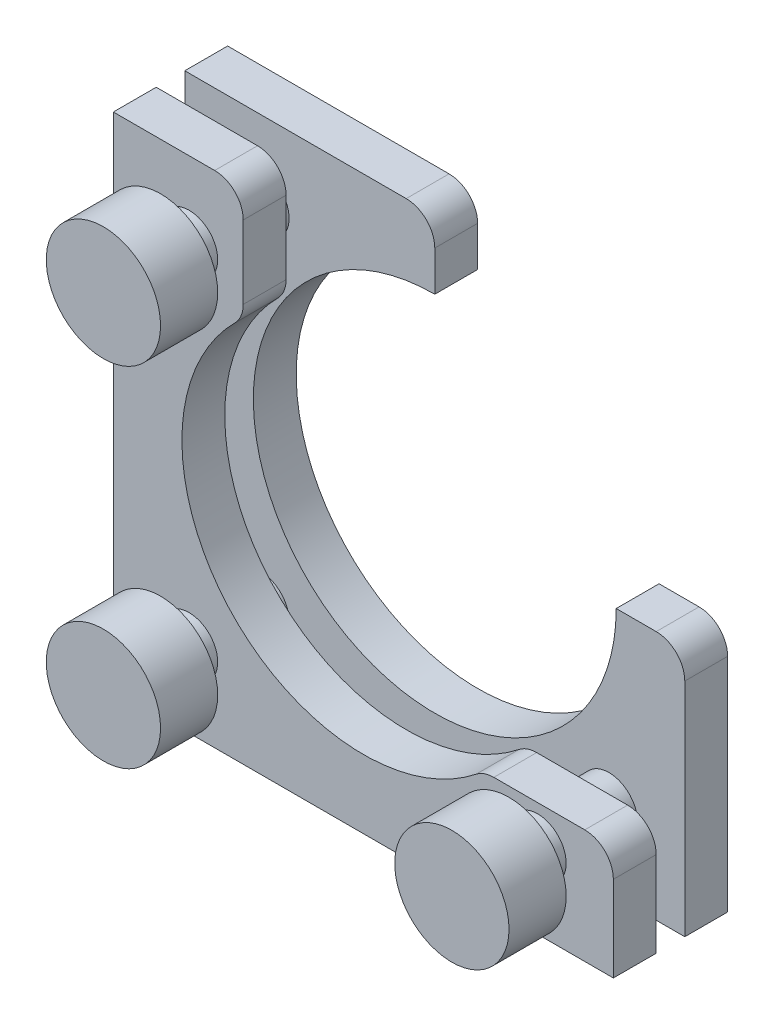
SolidWorks part; units mm, degrees
ref_plane "前视基准面" through (0, 0, 0) normal (0, 0, 1) x (1, 0, 0)
ref_plane "上视基准面" through (0, 0, 0) normal (0, 1, 0) x (1, 0, 0)
ref_plane "右视基准面" through (0, 0, 0) normal (1, 0, 0) x (0, 0, -1)
sketch "草图1" plane through (0, 0, 0) normal (0, 0, 1) x (1, 0, 0)
  line L1 (-17.5, 17.5) -> (17.5, 17.5)
  line L2 (-17.5, 17.5) -> (-17.5, -17.5)
  line L3 (-17.5, -17.5) -> (17.5, -17.5)
  line L4 (17.5, 17.5) -> (17.5, -17.5)
  line L5 (-17.5, 17.5) -> (17.5, -17.5) construction
  line L6 (-17.5, -17.5) -> (17.5, 17.5) construction
  circle A0 centre (0, 0) radius 12.7
  point P0 (0, 0)
  dimension "D1" = 25.4
  dimension "D2" = 35
  dimension "D3" = 35
extrude "凸台-拉伸1" add sketch "草图1" along normal blind 3
sketch "草图2" plane through (0, 0, 3) normal (0, 0, 1) x (1, 0, 0)
  line L0 (-17.5, 17.5) -> (17.5, -17.5)
  line L1 (17.5, -17.5) -> (17.5, 17.5)
  line L2 (17.5, 17.5) -> (-17.5, -17.5)
  circle A0 centre (-17.5, 17.5) radius 7.5
  circle A1 centre (-17.5, -17.5) radius 7.5
  circle A2 centre (17.5, -17.5) radius 7.5
  circle A3 centre (-12.1967, 12.1967) radius 2
  circle A4 centre (12.1967, -12.1967) radius 2
  circle A5 centre (-12.1967, -12.1967) radius 2
  dimension "D1" = 15
  dimension "D2" = 15
  dimension "D3" = 15
extrude "凸台-拉伸2" add sketch "草图2" along normal blind 2 and the other way blind 5 contours A3 | A5 | A4
sketch "草图3" plane through (0, 0, 5) normal (0, 0, 1) x (1, 0, 0)
  circle A0 centre (-12.1967, 12.1967) radius 4
  circle A1 centre (-12.1967, -12.1967) radius 4
  circle A2 centre (12.1967, -12.1967) radius 4
extrude "凸台-拉伸3" add sketch "草图3" along normal blind 4
sketch "草图4" plane through (0, 0, -2) normal (0, 0, -1) x (-1, 0, 0)
  line L1 (-17.5, -17.5) -> (17.5, -17.5)
  line L2 (-17.5, -17.5) -> (-17.5, 17.5)
  line L3 (-17.5, 17.5) -> (17.5, 17.5)
  line L4 (17.5, -17.5) -> (17.5, 17.5)
  line L5 (-17.5, -17.5) -> (17.5, 17.5) construction
  line L6 (-17.5, 17.5) -> (17.5, -17.5) construction
  circle A0 centre (0, 0) radius 12.7
  point P0 (0, 0)
extrude "凸台-拉伸4" add sketch "草图4" along normal blind 3
sketch "草图5" plane through (0, 0, 3) normal (0, 0, 1) x (1, 0, 0)
  line L1 (43.4081, 44.5181) -> (-8.4081, 44.5181)
  line L2 (43.4081, 44.5181) -> (43.4081, -9.5181)
  line L3 (43.4081, -9.5181) -> (-8.4081, -9.5181)
  line L4 (-8.4081, 44.5181) -> (-8.4081, -9.5181)
  line L5 (43.4081, 44.5181) -> (-8.4081, -9.5181) construction
  line L6 (43.4081, -9.5181) -> (-8.4081, 44.5181) construction
  circle A0 centre (0, 0) radius 12.7 construction
  point P0 (17.5, 17.5)
extrude "切除-拉伸1" cut sketch "草图5" against normal blind 3
sketch "草图7" plane through (0, 0, -5) normal (0, 0, -1) x (-1, 0, 0)
  line L1 (0, 35) -> (-35, 35)
  line L2 (0, 35) -> (0, 0)
  line L3 (0, 0) -> (-35, 0)
  line L4 (-35, 35) -> (-35, 0)
  line L5 (0, 35) -> (-35, 0) construction
  line L6 (0, 0) -> (-35, 35) construction
  point P0 (-17.5, 17.5)
  dimension "D1" = 35
  dimension "D2" = 35
extrude "切除-拉伸3" cut sketch "草图7" against normal blind 3
fillet "圆角1" radius 2 6 edges at (17.5, -9.5181, 1.5) (8.4081, -9.5181, 1.5) (-8.4081, 9.5181, 1.5) (-8.4081, 17.5, 1.5) (0, 17.5, -3.5) (17.5, 0, -3.5)
